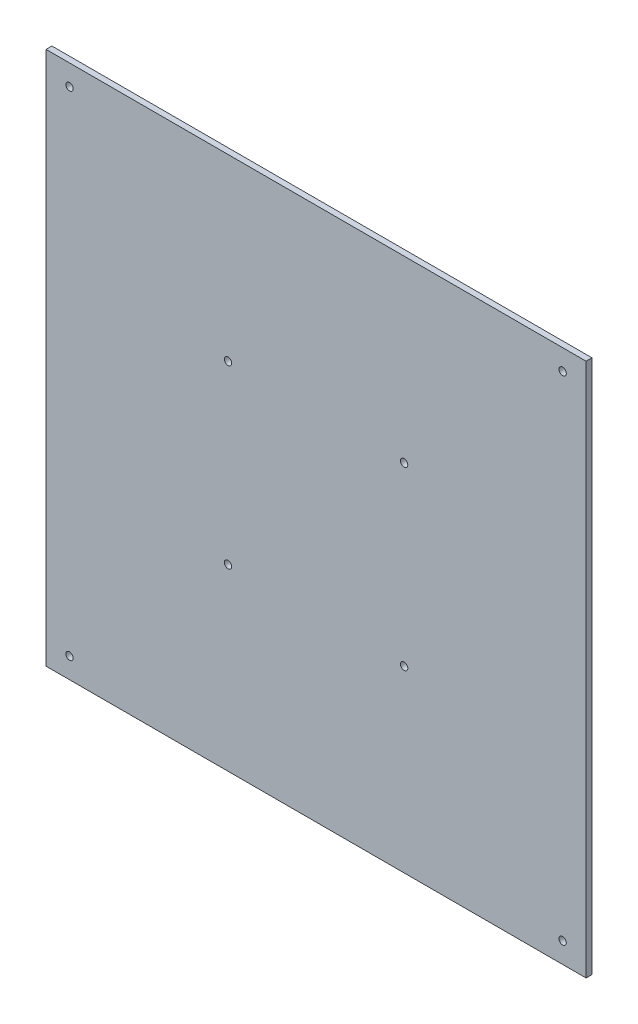
SolidWorks part; units mm, degrees
ref_plane "正面" through (0, 0, 0) normal (0, 0, 1) x (1, 0, 0)
ref_plane "平面" through (0, 0, 0) normal (0, 1, 0) x (1, 0, 0)
ref_plane "右側面" through (0, 0, 0) normal (1, 0, 0) x (0, 0, -1)
sketch "ｽｹｯﾁ1" plane through (0, 0, 0) normal (0, 0, 1) x (1, 0, 0)
  line L1 (0, 0) -> (184, 0)
  line L2 (0, 0) -> (0, 182)
  line L3 (0, 182) -> (184, 182)
  line L4 (184, 0) -> (184, 182)
  dimension "D1" = 182
  dimension "D2" = 184
extrude "ﾎﾞｽ - 押し出し1" add sketch "ｽｹｯﾁ1" along normal blind 2
hole_wizard "M3x0.5 ねじ穴1" positions "ｽｹｯﾁ2" profile "ｽｹｯﾁ3" tap size "M3x0.5" standard "JIS" end condition through all
sketch "ｽｹｯﾁ2" plane through (0, 0, 2) normal (0, 0, 1) x (1, 0, 0)
  line L0 (0, 182) -> (0, 0) construction
  line L2 (0, 0) -> (184, 0) construction
  line L3 (184, 0) -> (184, 182) construction
  line L4 (184, 182) -> (0, 182) construction
  point P0 (8, 175)
  point P2 (8, 7)
  point P4 (176, 7)
  point P6 (176, 175)
  dimension "D1" = 8
  dimension "D2" = 7
  dimension "D3" = 7
  dimension "D4" = 8
  dimension "D5" = 7
  dimension "D6" = 8
  dimension "D7" = 7
  dimension "D8" = 8
  dimension "D9" = 168
  dimension "D10" = 168
sketch "ｽｹｯﾁ3" plane through (8, 175, 2) normal (1, 0, 0) x (0, -1, 0)
  line L0 (0, 0) -> (0, 2)
  line L1 (0, 2) -> (1.25, 2)
  line L2 (1.25, 2) -> (1.25, 0)
  line L5 (1.25, 0) -> (0, 0)
  line L11 (0, -6.35) -> (0, 107.95) construction
  dimension "次ｻｰﾌｪｽまでのねじ下穴ﾄﾞﾘﾙ直径" = 2.5
  dimension "次ｻｰﾌｪｽまでのねじ下穴ﾄﾞﾘﾙの深さ" = 2
cosmetic thread "穴のねじ山1" parameters "D2"=3
cosmetic thread "穴のねじ山2" parameters "D2"=3
cosmetic thread "穴のねじ山3" parameters "D2"=3
cosmetic thread "穴のねじ山4" parameters "D2"=3
ref_plane "平面1" through (92, 0, 0) normal (1, 0, 0) x (0, 0, -1)
ref_plane "平面2" through (0, 91, 0) normal (0, 1, 0) x (1, 0, 0)
hole_wizard "M3x0.5 ねじ穴2" positions "ｽｹｯﾁ6" profile "ｽｹｯﾁ7" tap size "M3x0.5" standard "JIS" end condition through all
sketch "ｽｹｯﾁ6" plane through (0, 0, 2) normal (0, 0, 1) x (1, 0, 0)
  line L0 (1.1, 0) -> (-1.1, 0) construction
  line L1 (92, -1.1) -> (92, 1.1) construction
  point P0 (62, 61)
  point P3 (62, 121)
  dimension "D1" = 60
  dimension "D2" = 61
  dimension "D3" = 30
sketch "ｽｹｯﾁ7" plane through (62, 61, 2) normal (1, 0, 0) x (0, -1, 0)
  line L0 (0, 0) -> (0, 2)
  line L1 (0, 2) -> (1.25, 2)
  line L2 (1.25, 2) -> (1.25, 0)
  line L5 (1.25, 0) -> (0, 0)
  line L11 (0, -6.35) -> (0, 107.95) construction
  dimension "次ｻｰﾌｪｽまでのねじ下穴ﾄﾞﾘﾙ直径" = 2.5
  dimension "次ｻｰﾌｪｽまでのねじ下穴ﾄﾞﾘﾙの深さ" = 2
cosmetic thread "穴のねじ山5" parameters "D2"=3
cosmetic thread "穴のねじ山6" parameters "D2"=3
mirror "ﾐﾗｰ1" about plane through (92, 0, 0) normal (1, 0, 0) of "M3x0.5 ねじ穴2"
